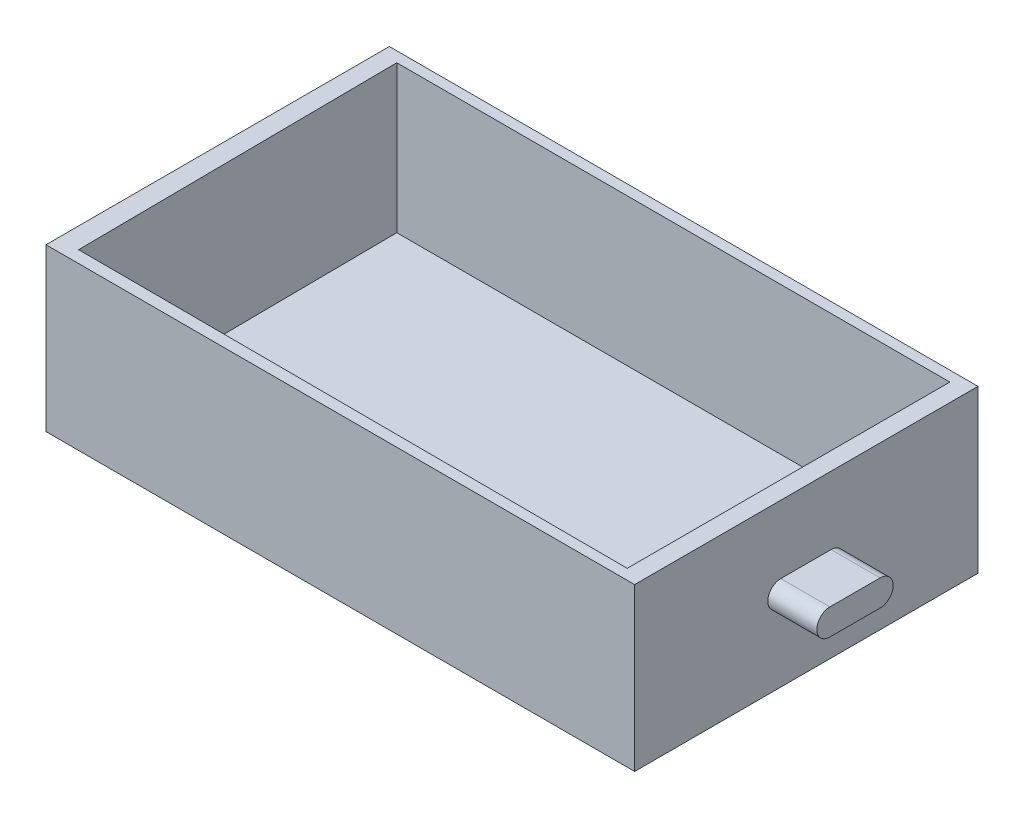
SolidWorks part; units mm, degrees
ref_plane "前视基准面" through (0, 0, 0) normal (0, 0, 1) x (1, 0, 0)
ref_plane "上视基准面" through (0, 0, 0) normal (0, 1, 0) x (1, 0, 0)
ref_plane "右视基准面" through (0, 0, 0) normal (1, 0, 0) x (0, 0, -1)
sketch "草图1" plane through (0, 0, 0) normal (0, 1, 0) x (1, 0, 0)
  line L1 (-60, 35) -> (60, 35)
  line L2 (-60, 35) -> (-60, -35)
  line L3 (-60, -35) -> (60, -35)
  line L4 (60, 35) -> (60, -35)
  line L5 (-60, 35) -> (60, -35) construction
  line L6 (-60, -35) -> (60, 35) construction
  point P0 (0, 0)
  dimension "D1" = 120
  dimension "D2" = 70
extrude "凸台-拉伸1" add sketch "草图1" along normal blind 3
sketch "草图3" plane through (0, 0, 0) normal (0, 1, 0) x (1, 0, 0)
  line L0 (-56.3721, 32.8837) -> (56.3721, 32.8837)
  line L1 (56.3721, 32.8837) -> (56.3721, -32.8837)
  line L2 (56.3721, -32.8837) -> (-55.8, -32.55)
  line L3 (-55.8, -32.55) -> (-56.3721, 32.8837)
  line L4 (-60, 35) -> (60, 35)
  line L5 (60, 35) -> (60, -35)
  line L6 (60, -35) -> (-60, -35)
  line L7 (-60, -35) -> (-60, 35)
  point P8 (-56.3721, 32.8837)
  point P9 (56.3721, 32.8837)
  point P10 (56.3721, -32.8837)
  point P11 (-55.8, -32.55)
extrude "凸台-拉伸2" add sketch "草图3" along normal blind 33
ref_plane "基准面4" through (60, 0, 0) normal (1, 0, 0) x (0, 0, -1)
sketch "草图4" plane through (60, 0, 0) normal (1, 0, 0) x (0, 0, -1)
  line L0 (-5.1989, 16.5) -> (5.0377, 16.5) construction
  line L1 (-5.1989, 19.1599) -> (5.0377, 19.1599)
  line L2 (-5.1989, 13.8401) -> (5.0377, 13.8401)
  arc A0 (-5.1989, 19.1599) -> (-5.1989, 13.8401) centre (-5.1989, 16.5) ccw
  arc A1 (5.0377, 13.8401) -> (5.0377, 19.1599) centre (5.0377, 16.5) ccw
  point P0 (0, 16.5)
  point P3 (-0.0806, 16.5)
extrude "凸台-拉伸3" add sketch "草图4" along normal blind 10
